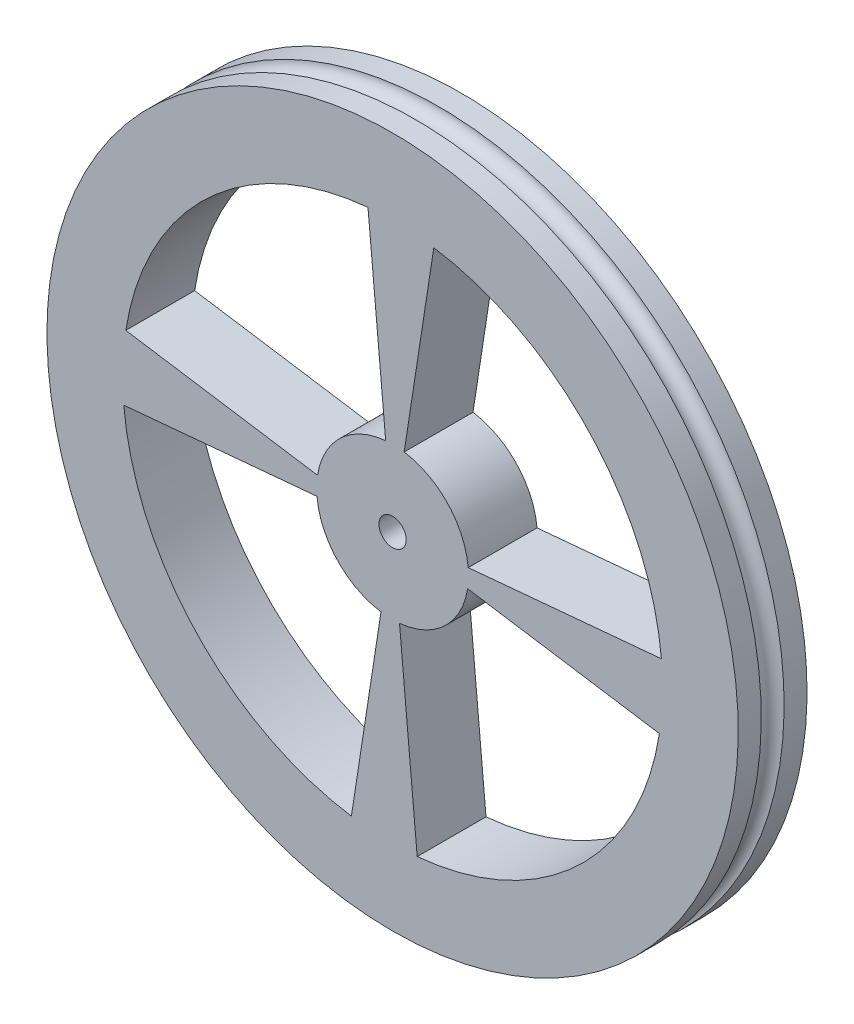
SolidWorks part; units mm, degrees
ref_plane "Front Plane" through (0, 0, 0) normal (0, 0, 1) x (1, 0, 0)
ref_plane "Top Plane" through (0, 0, 0) normal (0, 1, 0) x (1, 0, 0)
ref_plane "Right Plane" through (0, 0, 0) normal (1, 0, 0) x (0, 0, -1)
sketch "Sketch3" plane through (0, 0, 0) normal (1, 0, 0) x (0, 0, -1)
  line L0 (0, 0) -> (0, 53.34)
  line L1 (0, 53.34) -> (10.62, 53.34)
  line L2 (10.62, 53.34) -> (10.62, 0)
  line L3 (10.62, 0) -> (7.08, 0)
  line L4 (3.5494, 0) -> (0, 0)
  arc A0 (7.08, 0) -> (3.5494, 0) centre (5.3147, 0) ccw
  dimension "D2" = 1.7653
  dimension "D1" = 53.34
  dimension "D3" = 10.62
  dimension "D4" = 3.54
revolve "Revolve1" add sketch "Sketch3" angle 360 about L1
sketch "Sketch5" plane through (0, 0, 0) normal (0, 0, 1) x (1, 0, 0)
  circle A0 centre (0, 53.34) radius 2.1
  dimension "D1" = 4.2
  dimension "D2" = 53.34
extrude "Cut-Extrude1" cut sketch "Sketch5" against normal through all contours A0
sketch "Sketch6" plane through (0, 0, 0) normal (0, 0, 1) x (1, 0, 0)
  line L0 (6.3589, 94.5084) -> (1.7887, 64.9204)
  line L1 (11.669, 54.4078) -> (41.4833, 57.1362)
  line L2 (41.1684, 46.9811) -> (11.5804, 51.5513)
  line L3 (1.0678, 41.671) -> (3.7962, 11.8567)
  line L4 (-6.3589, 12.1716) -> (-1.7887, 41.7596)
  line L5 (-11.669, 52.2722) -> (-41.4833, 49.5438)
  line L6 (-41.1684, 59.6989) -> (-11.5804, 55.1287)
  line L7 (-1.0678, 65.009) -> (-3.7962, 94.8233)
  arc A0 (11.669, 54.4078) -> (1.7887, 64.9204) centre (0, 53.34) ccw
  arc A1 (6.3589, 94.5084) -> (41.4833, 57.1362) centre (0, 53.34) cw
  arc A2 (1.0678, 41.671) -> (11.5804, 51.5513) centre (0, 53.34) ccw
  arc A3 (41.1684, 46.9811) -> (3.7962, 11.8567) centre (0, 53.34) cw
  arc A4 (-11.669, 52.2722) -> (-1.7887, 41.7596) centre (0, 53.34) ccw
  arc A5 (-6.3589, 12.1716) -> (-41.4833, 49.5438) centre (0, 53.34) cw
  arc A6 (-1.0678, 65.009) -> (-11.5804, 55.1287) centre (0, 53.34) ccw
  arc A7 (-41.1684, 59.6989) -> (-3.7962, 94.8233) centre (0, 53.34) cw
  point P21 (0, 53.34)
  dimension "D1" = 4
extrude "Cut-Extrude2" cut sketch "Sketch6" against normal through all
